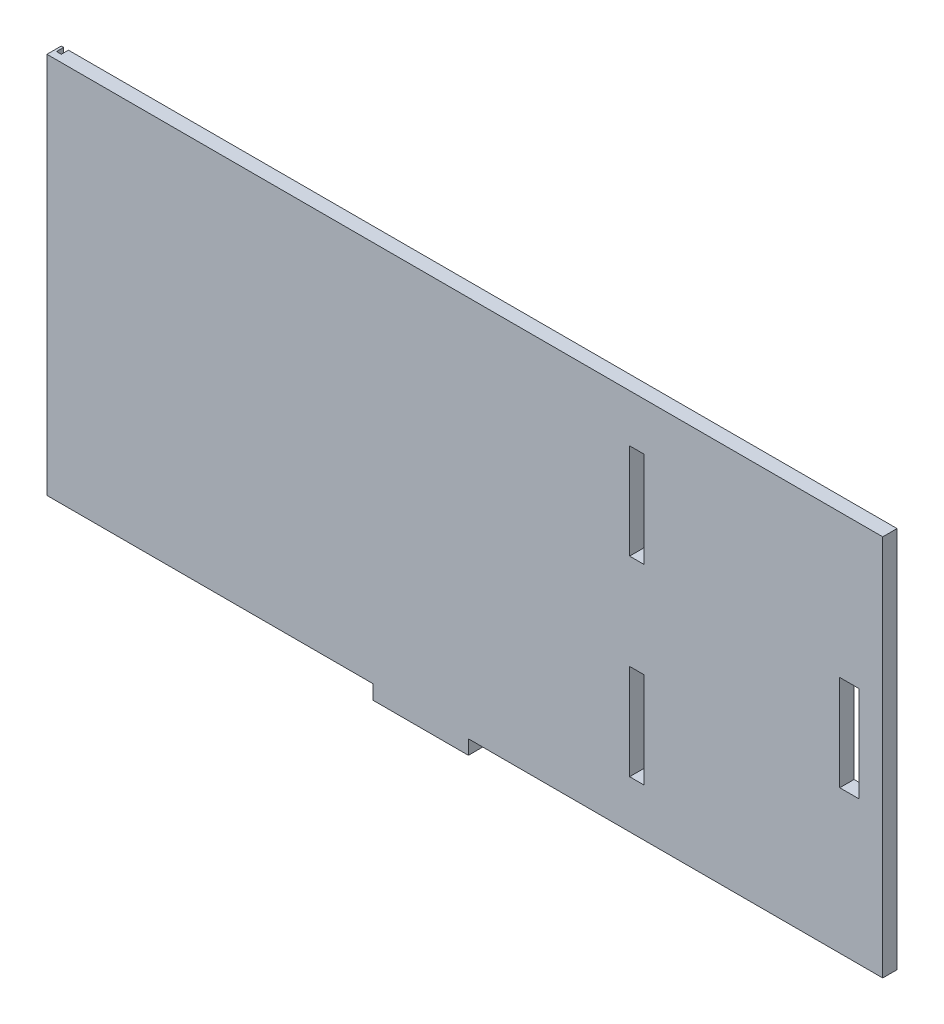
SolidWorks part; units mm, degrees
ref_plane "Plan de face" through (0, 0, 0) normal (0, 0, 1) x (1, 0, 0)
ref_plane "Plan de dessus" through (0, 0, 0) normal (0, 1, 0) x (1, 0, 0)
ref_plane "Plan de droite" through (0, 0, 0) normal (1, 0, 0) x (0, 0, -1)
sketch "Esquisse2" plane through (0, 0, 0) normal (0, 0, 1) x (1, 0, 0)
  line L1 (0, 0) -> (-175, 0)
  line L2 (0, 0) -> (0, -80)
  line L3 (0, -80) -> (-175, -80)
  line L4 (-175, 0) -> (-175, -80)
  dimension "D1" = 175
  dimension "D2" = 80
extrude "Boss.-Extru.2" add sketch "Esquisse2" along normal blind 3
sketch "Esquisse3" plane through (0, 0, 3) normal (0, 0, 1) x (1, 0, 0)
  line L0 (-53, -70) -> (-50, -70)
  line L1 (-53, -30) -> (-50, -30)
  line L2 (-53, -30) -> (-53, -10)
  line L3 (-53, -10) -> (-50, -10)
  line L4 (-50, -30) -> (-50, -10)
  line L5 (-53, -70) -> (-53, -50)
  line L6 (-53, -50) -> (-50, -50)
  line L7 (-50, -70) -> (-50, -50)
  line L8 (0, 0) -> (-175, 0) construction
  line L9 (0, -80) -> (0, 0) construction
  dimension "D1" = 3
  dimension "D2" = 20
  dimension "D3" = 20
  dimension "D4" = 20
  dimension "D5" = 3
  dimension "D6" = 10
  dimension "D7" = 50
extrude "Enlèv. mat.-Extru.1" cut sketch "Esquisse3" against normal up to next
sketch "Esquisse4" plane through (0, 0, 0) normal (0, 1, 0) x (1, 0, 0)
  line L0 (0, 0) -> (-175, 0) construction
  line L1 (-174.5, 0) -> (-173.5, 0)
  line L2 (-174.5, 0) -> (-174.5, -1.5)
  line L3 (-174.5, -1.5) -> (-173.5, -1.5)
  line L4 (-173.5, 0) -> (-173.5, -1.5)
  line L5 (-175, -3) -> (-175, 0) construction
  dimension "D1" = 1.5
  dimension "D2" = 1
  dimension "D3" = 0.5
extrude "Enlèv. mat.-Extru.2" cut sketch "Esquisse4" against normal up to next
sketch "Esquisse5" plane through (0, -80, 0) normal (0, -1, 0) x (-1, 0, 0)
  line L0 (0, 0) -> (86.75, 0) construction
  line L2 (173.5, 0) -> (0, 0) construction
  line L3 (175, -3) -> (0, -3) construction
  line L4 (86.75, 0) -> (106.75, 0)
  line L5 (86.75, 0) -> (86.75, -3)
  line L6 (86.75, -3) -> (106.75, -3)
  line L7 (106.75, 0) -> (106.75, -3)
  dimension "D1" = 20
extrude "Boss.-Extru.3" add sketch "Esquisse5" along normal blind 3
sketch "Esquisse6" plane through (0, 0, 0) normal (0, 0, -1) x (-1, 0, 0)
  line L0 (0, 0) -> (173.5, 0) construction
  line L1 (5, -30) -> (9, -30)
  line L2 (5, -30) -> (5, -50)
  line L3 (5, -50) -> (9, -50)
  line L4 (9, -30) -> (9, -50)
  line L5 (0, -80) -> (0, 0) construction
  dimension "D1" = 20
  dimension "D2" = 4
  dimension "D3" = 30
  dimension "D4" = 5
extrude "Enlèv. mat.-Extru.3" cut sketch "Esquisse6" against normal blind 10
